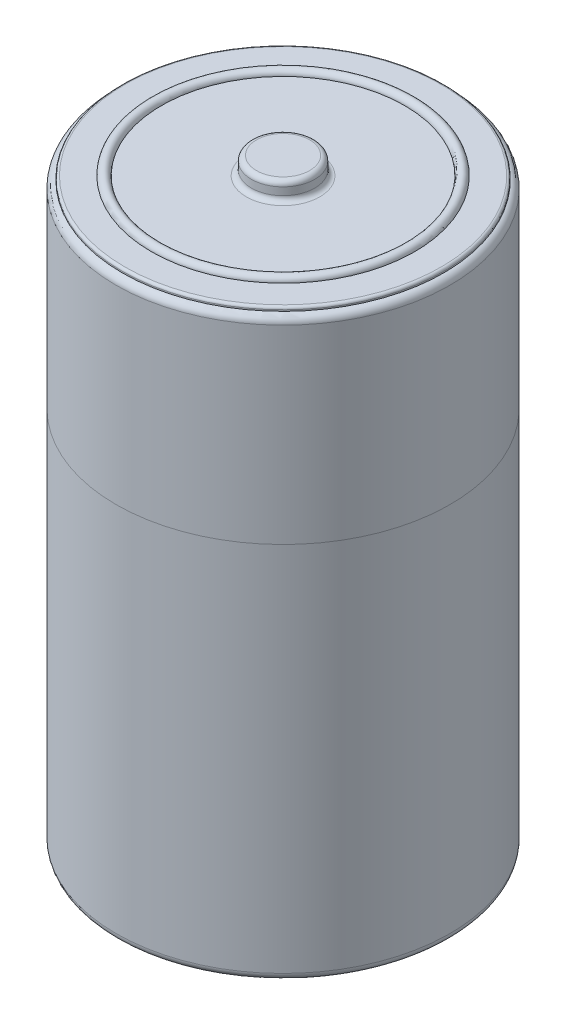
SolidWorks part; units mm, degrees
ref_plane "Front" through (0, 0, 0) normal (0, 0, 1) x (1, 0, 0)
ref_plane "Top" through (0, 0, 0) normal (0, 1, 0) x (1, 0, 0)
ref_plane "Right" through (0, 0, 0) normal (1, 0, 0) x (0, 0, -1)
sketch "Sketch1" plane through (0, 0, 0) normal (0, 0, 1) x (1, 0, 0)
  line L0 (0, 0) -> (0, -60.7104) construction
  line L1 (0, 0) -> (2.667, 0)
  line L2 (3.175, -0.508) -> (3.175, -1.27)
  line L3 (15.1007, -59.992) -> (15.1007, -60.246)
  line L4 (16.75, -2.921) -> (16.75, -59.23)
  line L5 (15.988, -59.992) -> (15.1007, -59.992)
  line L6 (0, 0) -> (0, -60.246)
  line L7 (13.208, -1.778) -> (15.861, -1.778)
  line L8 (3.683, -1.778) -> (12.192, -1.778)
  line L9 (15.1007, -60.246) -> (11.938, -60.246)
  line L10 (11.684, -60.5) -> (4.064, -60.5)
  line L11 (3.81, -60.246) -> (0, -60.246)
  line L12 (16.115, -2.032) -> (16.115, -2.1697)
  arc A0 (15.988, -59.992) -> (16.75, -59.23) centre (15.988, -59.23) ccw
  arc A1 (16.75, -2.921) -> (16.115, -2.1697) centre (15.988, -2.921) ccw
  arc A2 (13.208, -1.778) -> (12.192, -1.778) centre (12.7, -1.778) ccw
  arc A3 (3.175, -0.508) -> (2.667, 0) centre (2.667, -0.508) ccw
  arc A4 (3.683, -1.778) -> (3.175, -1.27) centre (3.683, -1.27) cw
  arc A5 (11.938, -60.246) -> (11.684, -60.5) centre (11.684, -60.246) cw
  arc A6 (4.064, -60.5) -> (3.81, -60.246) centre (3.81, -60.5) ccw
  arc A7 (16.115, -2.032) -> (15.861, -1.778) centre (15.861, -2.032) ccw
  dimension "D1" = 0.762
  dimension "D6" = 0.508
  dimension "D7" = 0.254
  dimension "D8" = 0.508
  dimension "D9" = 12.7
  dimension "D11" = 0.254
  dimension "D15" = 0.127
  dimension "D2" = 1.778
  dimension "D3" = 6.35
  dimension "D4" = 33.5
  dimension "D5" = 60.5
  dimension "D10" = 0.254
  dimension "D12" = 7.62
  dimension "D13" = 3.81
  dimension "D14" = 0.381
  dimension "D16" = 30.2014
revolve "Base-Revolve" add sketch "Sketch1" angle 360 about L0
sketch "Sketch2" plane through (0, 0, 0) normal (0, 0, 1) x (1, 0, 0)
  line L0 (-24.6879, -21.971) -> (24.2265, -21.971)
  line L1 (16.75, -2.921) -> (-16.75, -2.921) construction
  dimension "D1" = 19.05
split line "Split Line1"
